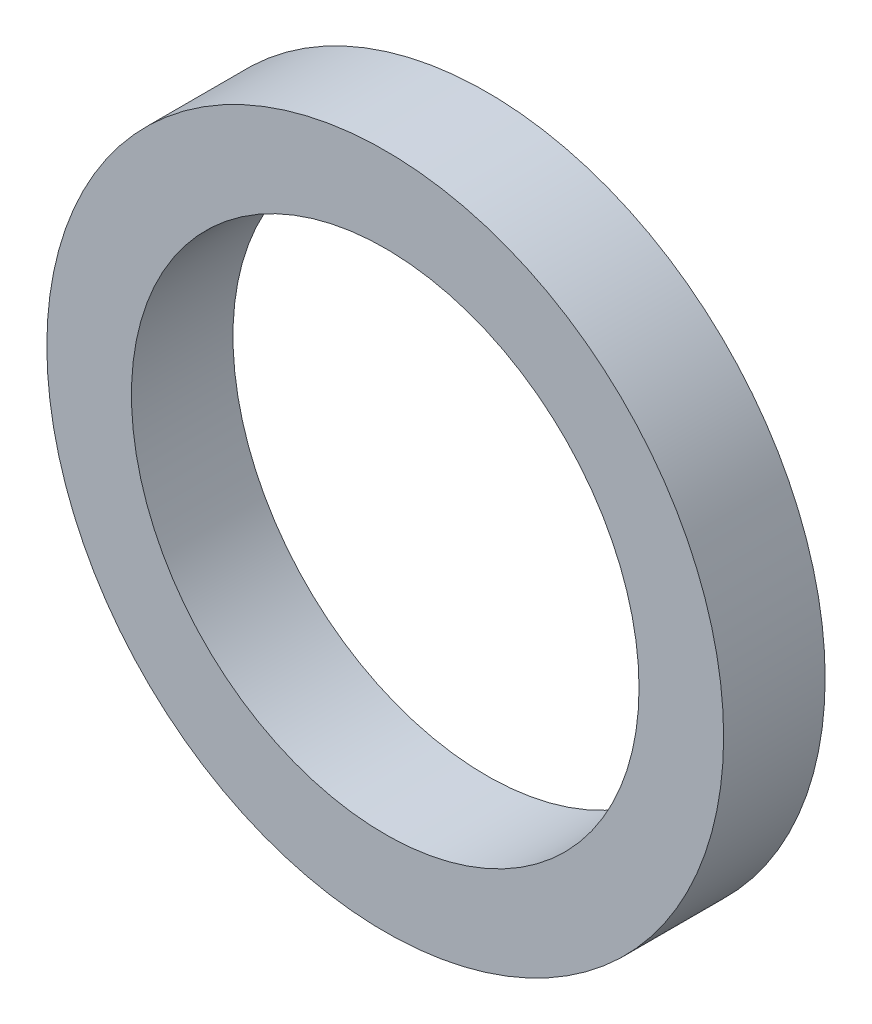
SolidWorks part; units mm, degrees
ref_plane "Front Plane" through (0, 0, 0) normal (0, 0, 1) x (1, 0, 0)
ref_plane "Top Plane" through (0, 0, 0) normal (0, 1, 0) x (1, 0, 0)
ref_plane "Right Plane" through (0, 0, 0) normal (1, 0, 0) x (0, 0, -1)
sketch "Sketch1" plane through (0, 0, 0) normal (0, 0, 1) x (1, 0, 0)
  circle A0 centre (0, 0) radius 100
  circle A1 centre (0, 0) radius 75
  dimension "D1" = 200
  dimension "D2" = 150
extrude "Boss-Extrude1" add sketch "Sketch1" along normal blind 30
